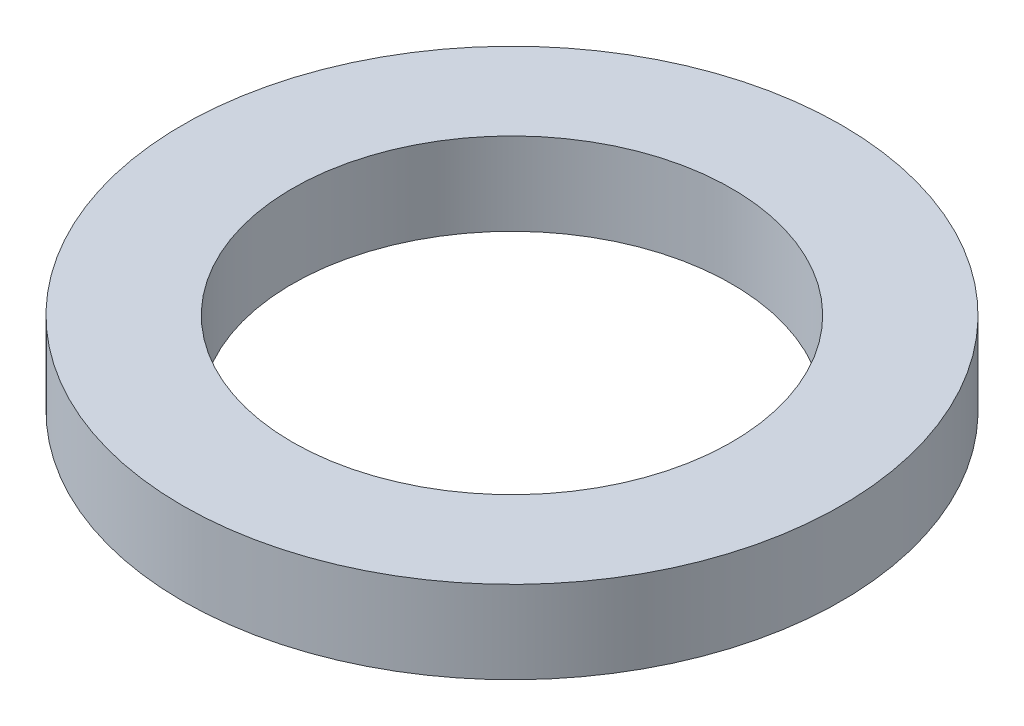
SolidWorks part; units mm, degrees
ref_plane "Front Plane" through (0, 0, 0) normal (0, 0, 1) x (1, 0, 0)
ref_plane "Top Plane" through (0, 0, 0) normal (0, 1, 0) x (1, 0, 0)
ref_plane "Right Plane" through (0, 0, 0) normal (1, 0, 0) x (0, 0, -1)
sketch "Sketch1" plane through (0, 0, 0) normal (0, 1, 0) x (1, 0, 0)
  circle A0 centre (0, 0) radius 4.7625
  dimension "OD" = 9.525
extrude "Boss-Extrude1" add sketch "Sketch1" along normal blind 1.1938
sketch "Sketch5" plane through (0, 1.1938, 0) normal (0, 1, 0) x (-1, 0, 0)
  circle A0 centre (0, 0) radius 3.175
  dimension "ID" = 6.35
extrude "Cut-Extrude1" cut sketch "Sketch5" against normal through all
